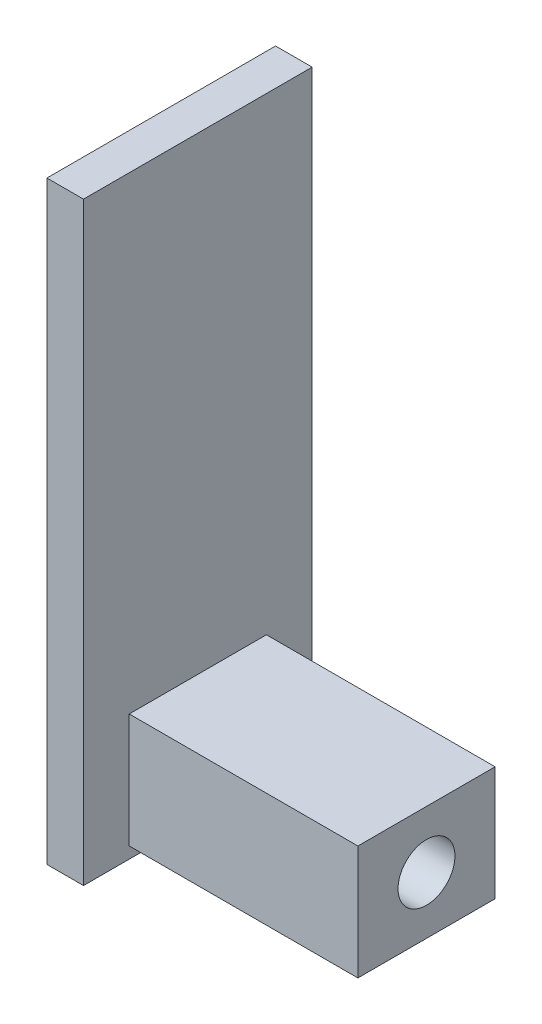
SolidWorks part; units mm, degrees
ref_plane "Front Plane" through (0, 0, 0) normal (0, 0, 1) x (1, 0, 0)
ref_plane "Top Plane" through (0, 0, 0) normal (0, 1, 0) x (1, 0, 0)
ref_plane "Right Plane" through (0, 0, 0) normal (1, 0, 0) x (0, 0, -1)
sketch "Sketch2" plane through (0, 0, 0) normal (1, 0, 0) x (0, 0, -1)
  line L1 (0, 0) -> (50, 0)
  line L2 (0, 0) -> (0, 130)
  line L3 (0, 130) -> (50, 130)
  line L4 (50, 0) -> (50, 130)
  dimension "D1" = 50
  dimension "D2" = 130
extrude "Boss-Extrude2" add sketch "Sketch2" along normal blind 8
sketch "Sketch4" plane through (0, 0, 0) normal (1, 0, 0) x (0, 0, -1)
  line L0 (0, 0) -> (50, 0) construction
  line L1 (50, 0) -> (50, 130) construction
  circle A0 centre (25, 15) radius 11
  dimension "D1" = 15
  dimension "D2" = 25
extrude "Cut-Extrude1" cut sketch "Sketch4" against normal blind 20 and the other way blind 20
sketch "Sketch7" plane through (8, 0, 0) normal (1, 0, 0) x (0, 0, -1)
  line L0 (0, 0) -> (50, 0) construction
  line L1 (10, 27.5) -> (40, 27.5)
  line L2 (10, 27.5) -> (10, 2.5)
  line L3 (10, 2.5) -> (40, 2.5)
  line L4 (40, 27.5) -> (40, 2.5)
  circle A0 centre (25, 15) radius 11 construction
  point P4 (40, 15)
  dimension "D1" = 30
  dimension "D2" = 25
  dimension "D3" = 15
  dimension "D4" = 15
extrude "Boss-Extrude3" add sketch "Sketch7" along normal blind 50
sketch "Sketch8" plane through (58, 0, 0) normal (1, 0, 0) x (0, 0, -1)
  line L0 (40, 2.5) -> (40, 27.5) construction
  line L1 (0, 0) -> (50, 0) construction
  circle A0 centre (25, 15) radius 6.223
  dimension "D1" = 15
  dimension "D2" = 15
extrude "Cut-Extrude2" cut sketch "Sketch8" against normal blind 50
